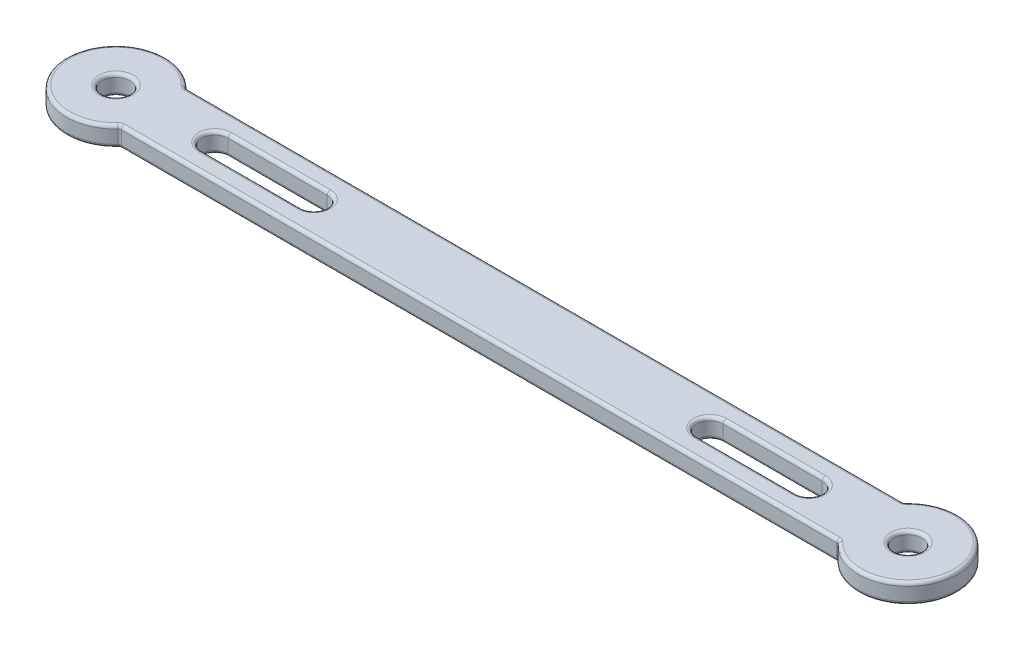
SolidWorks part; units mm, degrees
ref_plane "Front Plane" through (0, 0, 0) normal (0, 0, 1) x (1, 0, 0)
ref_plane "Top Plane" through (0, 0, 0) normal (0, 1, 0) x (1, 0, 0)
ref_plane "Right Plane" through (0, 0, 0) normal (1, 0, 0) x (0, 0, -1)
sketch "Sketch1" plane through (0, 0, 0) normal (0, 1, 0) x (1, 0, 0)
  line L0 (5.5902, 5) -> (114.4098, 5)
  line L1 (0, 0) -> (-35.7472, 0) construction
  line L2 (5.5902, -5) -> (114.4098, -5)
  circle A0 centre (0, 0) radius 2.1
  arc A1 (5.5902, 5) -> (5.5902, -5) centre (0, 0) ccw
  circle A2 centre (120, 0) radius 2.1
  arc A3 (114.4098, -5) -> (114.4098, 5) centre (120, 0) ccw
  dimension "D1" = 4.2
  dimension "D2" = 15
  dimension "D3" = 4.2
  dimension "D4" = 15
  dimension "D5" = 120
  dimension "D6" = 5
  dimension "D7" = 10
extrude "Boss-Extrude1" add sketch "Sketch1" along normal blind 3
sketch "Sketch2" plane through (0, 3, 0) normal (0, 1, 0) x (1, 0, 0)
  line L0 (15, 0) -> (30, 0) construction
  line L2 (15, 2) -> (30, 2)
  line L3 (15, -2) -> (30, -2)
  line L4 (60, 5) -> (60, -19.9612) construction
  line L5 (114.4098, 5) -> (5.5902, 5) construction
  line L6 (105, 0) -> (90, 0) construction
  line L7 (105, 2) -> (90, 2)
  line L8 (105, -2) -> (90, -2)
  arc A0 (15, 2) -> (15, -2) centre (15, 0) ccw
  arc A1 (30, -2) -> (30, 2) centre (30, 0) ccw
  arc A2 (105, 2) -> (105, -2) centre (105, 0) cw
  arc A3 (90, -2) -> (90, 2) centre (90, 0) cw
  point P5 (22.5, 0)
  point P14 (97.5, 0)
  dimension "D2" = 2
  dimension "D1" = 15
  dimension "D3" = 15
extrude "Cut-Extrude1" cut sketch "Sketch2" against normal through all
fillet "Fillet1" radius 0.5 32 edges at (127.5, 3, 0) (127.5, 0, 0) (-7.5, 3, 0) (-7.5, 0, 0) (88, 0, 0) (97.5, 0, -2) (107, 0, 0) (88, 3, 0) (97.5, 3, -2) (107, 3, 0) (13, 0, 0) (22.5, 0, -2) (32, 0, 0) (13, 3, 0) (22.5, 3, -2) (32, 3, 0) (97.5, 0, 2) (97.5, 3, 2) (5.5902, 1.5, 5) (60, 3, 5) (114.4098, 1.5, 5) (60, 0, 5) (0, 0, 2.1) (0, 3, 2.1) (120, 0, 2.1) (120, 3, 2.1) (22.5, 0, 2) (22.5, 3, 2) (114.4098, 1.5, -5) (60, 3, -5) (5.5902, 1.5, -5) (60, 0, -5)
